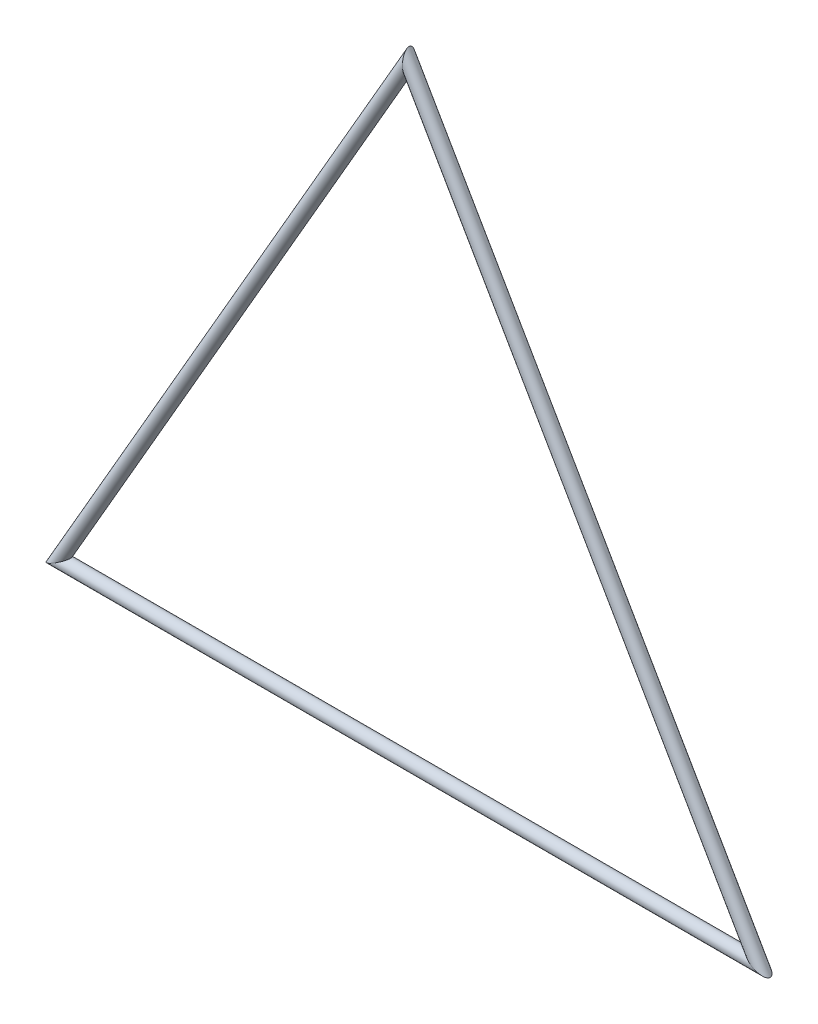
SolidWorks part; units mm, degrees
ref_plane "Front Plane" through (0, 0, 0) normal (0, 0, 1) x (1, 0, 0)
ref_plane "Top Plane" through (0, 0, 0) normal (0, 1, 0) x (1, 0, 0)
ref_plane "Right Plane" through (0, 0, 0) normal (1, 0, 0) x (0, 0, -1)
sketch "Sketch1" plane through (0, 0, 0) normal (0, 0, 1) x (1, 0, 0)
  line L0 (0, 0) -> (1524, 0)
  line L1 (762, 1319.8227) -> (0, 0)
  line L2 (1524, 0) -> (762, 1319.8227)
  dimension "D1" = 1524
  dimension "D2" = 60
  dimension "D3" = 60
other "Structural Member1"
ref_plane "Plane1" through (762, 1319.8227, 0) normal (-0.5, -0.866, 0) x (0.866, -0.5, 0)
sketch "Sketch11" plane through (762, 1319.8227, 0) normal (-0.5, -0.866, 0) x (0.866, -0.5, 0)
  circle A0 centre (0, 0) radius 14.3294
  point P0 (0, 0)
  point P5 (0, 0)
  dimension "D1" = 28.6588
